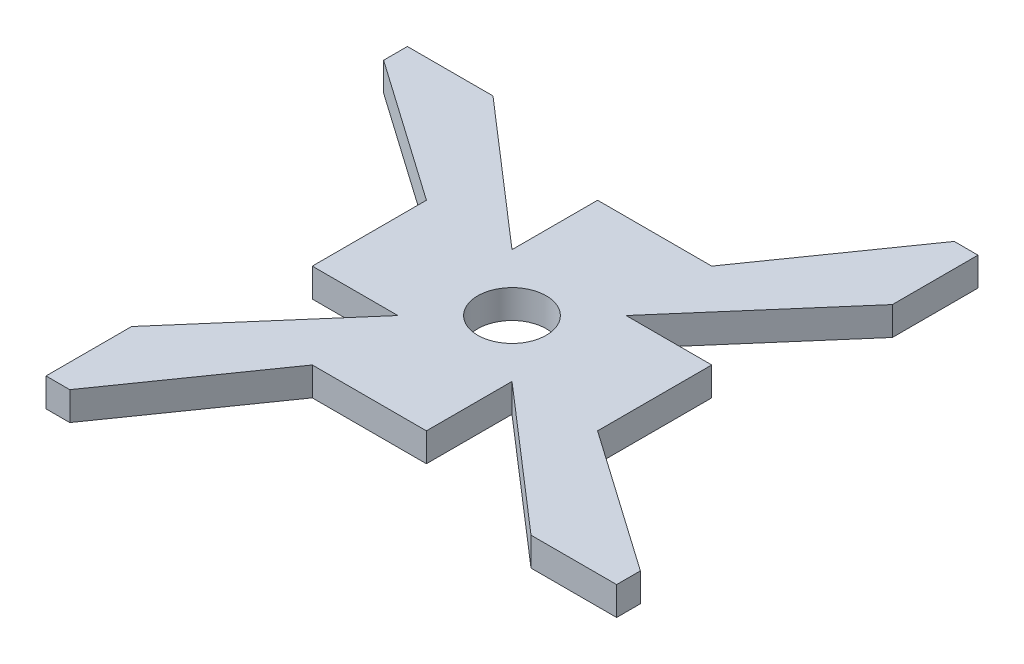
SolidWorks part; units mm, degrees
ref_plane "Front Plane" through (0, 0, 0) normal (0, 0, 1) x (1, 0, 0)
ref_plane "Top Plane" through (0, 0, 0) normal (0, 1, 0) x (1, 0, 0)
ref_plane "Right Plane" through (0, 0, 0) normal (1, 0, 0) x (0, 0, -1)
sketch "Sketch1" plane through (0, 0, 0) normal (0, 1, 0) x (1, 0, 0)
  line L0 (-21, 19) -> (-6, 6)
  line L5 (-6, 15) -> (6, 15)
  line L6 (-6, 15) -> (-6, -15)
  line L7 (-6, -15) -> (6, -15)
  line L8 (6, 15) -> (6, -15)
  line L9 (-15, 6) -> (15, 6)
  line L10 (-15, 6) -> (-15, -6)
  line L11 (-15, -6) -> (15, -6)
  line L12 (15, 6) -> (15, -6)
  line L13 (-30, 19) -> (-21, 19)
  line L14 (-30, 19) -> (-30, 16.5)
  line L15 (-30, 16.5) -> (-21, 16.5)
  line L16 (-21, 19) -> (-21, 16.5)
  line L17 (-30, 16.5) -> (-15, 6)
  line L18 (19, 30) -> (16.5, 30)
  line L19 (19, 30) -> (19, 21)
  line L20 (19, 21) -> (16.5, 21)
  line L21 (16.5, 30) -> (16.5, 21)
  line L22 (16.5, 30) -> (6, 15)
  line L23 (19, 21) -> (6, 6)
  line L24 (30, -19) -> (30, -16.5)
  line L25 (30, -19) -> (21, -19)
  line L26 (21, -19) -> (21, -16.5)
  line L27 (30, -16.5) -> (21, -16.5)
  line L28 (30, -16.5) -> (15, -6)
  line L29 (21, -19) -> (6, -6)
  line L30 (-19, -30) -> (-16.5, -30)
  line L31 (-19, -30) -> (-19, -21)
  line L32 (-19, -21) -> (-16.5, -21)
  line L33 (-16.5, -30) -> (-16.5, -21)
  line L34 (-16.5, -30) -> (-6, -15)
  line L35 (-19, -21) -> (-6, -6)
  circle A0 centre (0, 0) radius 3.6
  point P11 (-30, 19)
  point P38 (0, 0)
  dimension "D1" = 7.2
  dimension "D5" = 6
  dimension "D11" = 30
  dimension "D2" = 12
  dimension "D3" = 30
  dimension "D4" = 15
  dimension "D6" = 6
  dimension "D7" = 15
  dimension "D8" = 15
  dimension "D9" = 6
  dimension "D10" = 19
  dimension "D12" = 2.5
  dimension "D13" = 9
  dimension "D14" = 4
extrude "Boss-Extrude2" add sketch "Sketch1" along normal blind 3 contours L15 L17 L9 L0 L16 | L16 L13 L14 L15 | L6 L9 L8 L5 | L10 L11 L6 L9 | L6 L11 L8 L9 A0 | L12 L9 L8 L11 | L11 L6 L7 L8 | L35 L32 L33 L34 L6 | L30 L33 L32 L31 | L29 L26 L27 L28 L11 | L24 L27 L26 L25 | L23 L20 L21 L22 L8 | L18 L21 L20 L19
